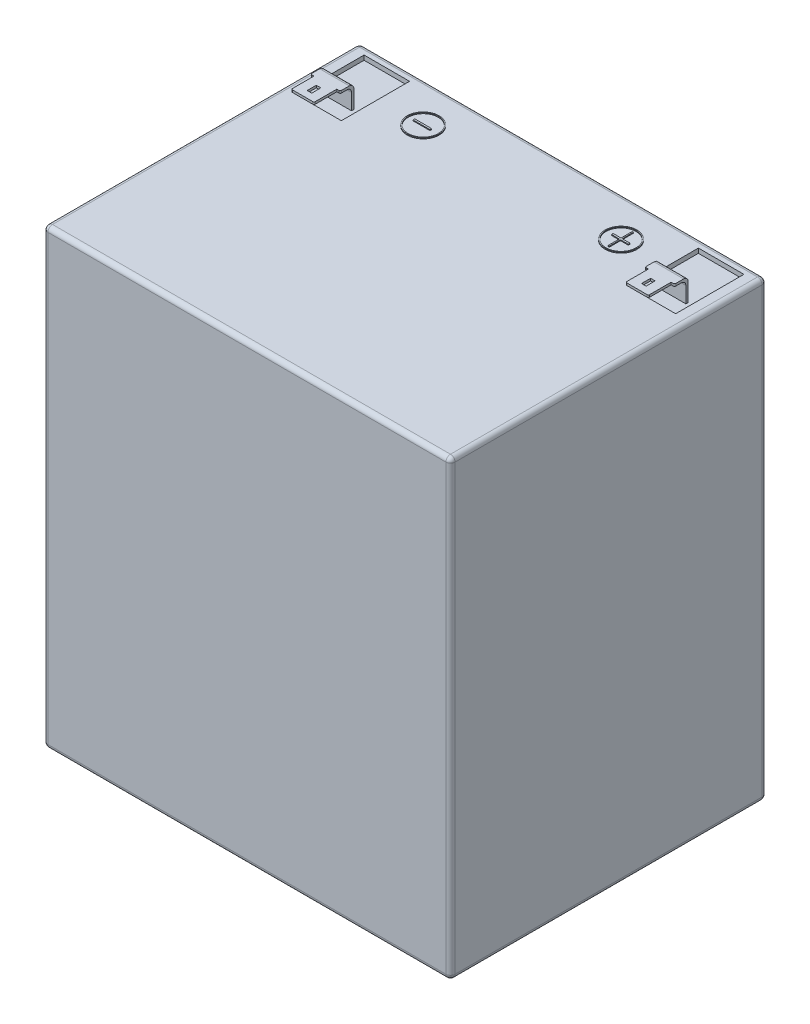
SolidWorks part; units mm, degrees
ref_plane "前视基准面" through (0, 0, 0) normal (0, 0, 1) x (1, 0, 0)
ref_plane "上视基准面" through (0, 0, 0) normal (0, 1, 0) x (1, 0, 0)
ref_plane "右视基准面" through (0, 0, 0) normal (1, 0, 0) x (0, 0, -1)
sketch "草图1" plane through (0, 0, 0) normal (0, 1, 0) x (1, 0, 0)
  line L1 (-44.75, -34.75) -> (44.75, -34.75)
  line L2 (-44.75, -34.75) -> (-44.75, 34.75)
  line L3 (-44.75, 34.75) -> (44.75, 34.75)
  line L4 (44.75, -34.75) -> (44.75, 34.75)
  line L5 (-44.75, -34.75) -> (44.75, 34.75) construction
  line L6 (-44.75, 34.75) -> (44.75, -34.75) construction
  point P0 (0, 0)
  dimension "D1" = 89.5
  dimension "D2" = 69.5
extrude "凸台-拉伸1" add sketch "草图1" along normal blind 99.5
sketch "草图2" plane through (0, 99.5, 0) normal (0, 1, 0) x (1, 0, 0)
  line L0 (0, 0) -> (0, 46.7187) construction
  line L1 (-41.75, 32.75) -> (-31.75, 32.75)
  line L2 (-41.75, 32.75) -> (-41.75, 17.75)
  line L3 (-41.75, 17.75) -> (-31.75, 17.75)
  line L4 (-31.75, 32.75) -> (-31.75, 17.75)
  line L5 (44.75, 34.75) -> (-44.75, 34.75) construction
  line L6 (-44.75, 34.75) -> (-44.75, -34.75) construction
  line L7 (41.75, 17.75) -> (31.75, 17.75)
  line L8 (41.75, 32.75) -> (41.75, 17.75)
  line L9 (41.75, 32.75) -> (31.75, 32.75)
  line L10 (31.75, 32.75) -> (31.75, 17.75)
  dimension "D1" = 2
  dimension "D2" = 3
  dimension "D3" = 10
  dimension "D4" = 15
extrude "切除-拉伸1" cut sketch "草图2" against normal blind 1
fillet "圆角1" radius 1 12 edges at (-44.75, 0, 0) (0, 0, 34.75) (0, 0, -34.75) (44.75, 0, 0) (44.75, 49.75, -34.75) (-44.75, 49.75, -34.75) (0, 99.5, -34.75) (-44.75, 99.5, 0) (44.75, 99.5, 0) (44.75, 49.75, 34.75) (-44.75, 49.75, 34.75) (0, 99.5, 34.75)
sketch "草图3" plane through (0, 98.5, 0) normal (0, 1, 0) x (1, 0, 0)
  line L0 (36.75, 17.75) -> (36.75, 26.1235) construction
  line L1 (40, 21.75) -> (33.5, 21.75)
  line L2 (40, 21.75) -> (40, 22.25)
  line L3 (40, 22.25) -> (33.5, 22.25)
  line L4 (33.5, 21.75) -> (33.5, 22.25)
  line L5 (31.75, 17.75) -> (41.75, 17.75) construction
  line L6 (31.75, 17.75) -> (41.75, 17.75) construction
  dimension "D1" = 0.5
  dimension "D2" = 6.5
  dimension "D3" = 4
extrude "凸台-拉伸2" add sketch "草图3" along normal blind 5
sketch "草图4" plane through (0, 103.5, 0) normal (0, 1, 0) x (1, 0, 0)
  line L0 (33.5, 21.75) -> (33.5, 19.25)
  line L1 (33.5, 19.25) -> (34.25, 19.25)
  line L2 (34.25, 19.25) -> (34.25, 14.25)
  line L3 (34.25, 14.25) -> (39.25, 14.25)
  line L4 (39.25, 14.25) -> (39.25, 19.25)
  line L5 (39.25, 19.25) -> (40, 19.25)
  line L6 (40, 19.25) -> (40, 21.75)
  line L8 (36.75, 21.75) -> (36.75, 7.3243) construction
  line L9 (40, 22.25) -> (33.5, 22.25) construction
  line L10 (31.75, 17.75) -> (41.75, 17.75) construction
  line L11 (36.25, 15.75) -> (37.25, 15.75)
  line L12 (36.25, 15.75) -> (36.25, 17.75)
  line L13 (36.25, 17.75) -> (37.25, 17.75)
  line L14 (37.25, 15.75) -> (37.25, 17.75)
  line L16 (33.5, 21.75) -> (40, 21.75)
  dimension "D1" = 5
  dimension "D2" = 8
  dimension "D3" = 3
  dimension "D4" = 1
  dimension "D5" = 2
extrude "凸台-拉伸3" add sketch "草图4" against normal blind 0.5
fillet "圆角2" radius 1 2 edges at (36.75, 103.5, -22.25) (36.75, 103, -21.75)
fillet "圆角3" radius 0.3 4 edges at (34.25, 103.25, -14.25) (33.5, 103.25, -19.25) (40, 103.25, -19.25) (39.25, 103.25, -14.25)
mirror "镜向1" about plane through (0, 0, 0) normal (1, 0, 0) of "凸台-拉伸2", "凸台-拉伸3", "圆角2", "圆角3"
sketch "草图5" plane through (0, 99.5, 0) normal (0, 1, 0) x (1, 0, 0)
  line L1 (0, 0) -> (0, 43.4982) construction
  text T0 "+" font "汉仪长仿宋体" height 6
  text T1 "-" font "汉仪长仿宋体" height 6
  point P3 (0, 0)
  point P4 (0, 0)
  point P17 (0, 0)
  point P18 (0, 0)
  point P21 (18.25, 22.25)
  point P22 (19.508, 23.1331)
  point P23 (-23.9503, 23.2906)
  point P24 (0, 0)
  point P25 (-23.944, 23.285)
  point P26 (-23.9698, 23.044)
  point P27 (-24.2076, 23.2579)
  point P28 (0, 0)
  point P29 (-24.1088, 23.1331)
extrude "凸台-拉伸4" add sketch "草图5" along normal blind 0.2
sketch "草图6" plane through (0, 99.5, 0) normal (0, 1, 0) x (1, 0, 0)
  line L0 (31.75, 32.75) -> (31.75, 17.75) construction
  line L1 (43.75, 33.75) -> (-43.75, 33.75) construction
  line L2 (0, 0) -> (0, 26.8919) construction
  circle A0 centre (21.75, 25.75) radius 3.5
  circle A1 centre (21.75, 25.75) radius 3.3
  circle A2 centre (-21.75, 25.75) radius 3.3
  circle A3 centre (-21.75, 25.75) radius 3.5
  point P14 (0, 0)
  dimension "D1" = 7
  dimension "D2" = 10
  dimension "D3" = 8
  dimension "D4" = 0.2
extrude "凸台-拉伸5" add sketch "草图6" along normal blind 0.2
